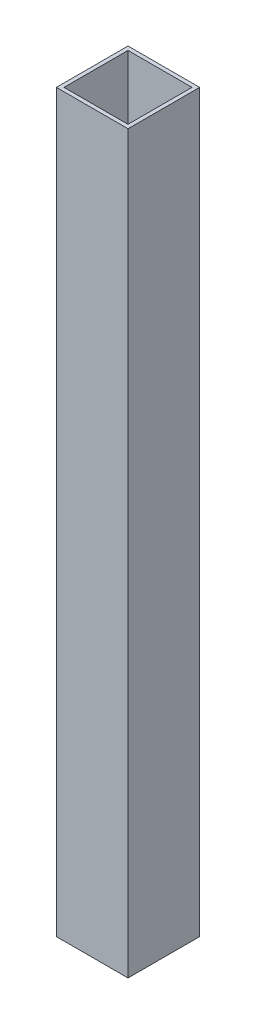
SolidWorks part; units mm, degrees
ref_plane "Plan de face" through (0, 0, 0) normal (0, 0, 1) x (1, 0, 0)
ref_plane "Plan de dessus" through (0, 0, 0) normal (0, 1, 0) x (1, 0, 0)
ref_plane "Plan de droite" through (0, 0, 0) normal (1, 0, 0) x (0, 0, -1)
sketch "Esquisse1" plane through (0, 0, 0) normal (0, 1, 0) x (1, 0, 0)
  line L0 (-6.7, 6.7) -> (6.7, 6.7)
  line L1 (-7.5, -7.5) -> (7.5, -7.5)
  line L2 (-7.5, -7.5) -> (-7.5, 7.5)
  line L3 (-7.5, 7.5) -> (7.5, 7.5)
  line L4 (7.5, -7.5) -> (7.5, 7.5)
  line L5 (-7.5, -7.5) -> (7.5, 7.5) construction
  line L6 (-7.5, 7.5) -> (7.5, -7.5) construction
  line L7 (6.7, -6.7) -> (6.7, 6.7)
  line L8 (-6.7, -6.7) -> (6.7, -6.7)
  line L9 (-6.7, -6.7) -> (-6.7, 6.7)
  point P0 (0, 0)
  dimension "D1" = 15
  dimension "D2" = 15
  dimension "D3" = 0.8
extrude "Boss.-Extru.1" add sketch "Esquisse1" along normal blind 154
